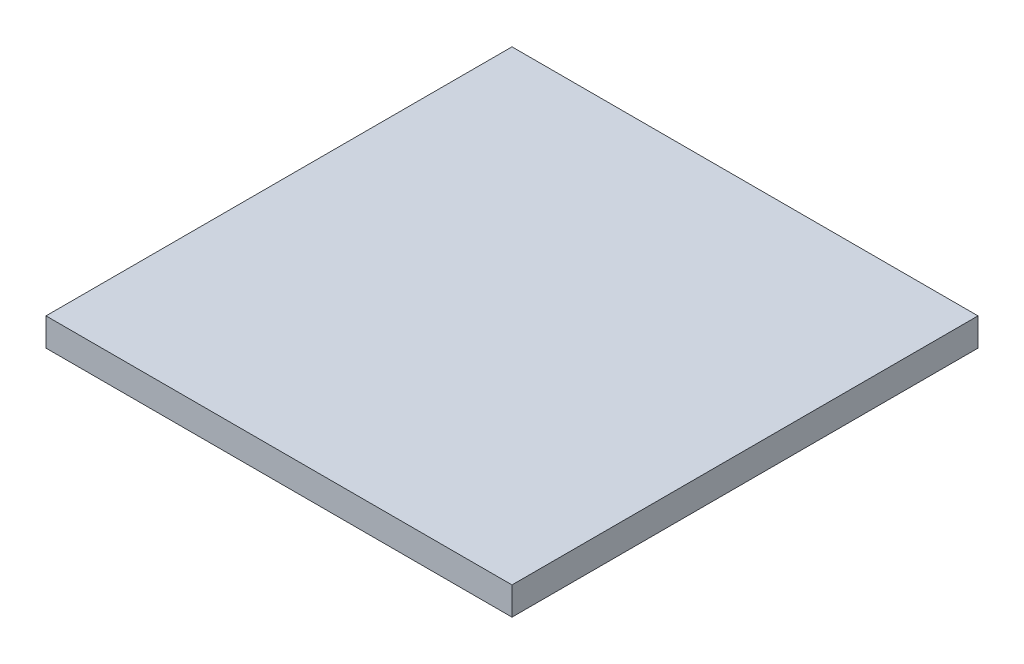
SolidWorks part; units mm, degrees
material "Acrylic (Medium-high impact)"
ref_plane "Front Plane" through (0, 0, 0) normal (0, 0, 1) x (1, 0, 0)
ref_plane "Top Plane" through (0, 0, 0) normal (0, 1, 0) x (1, 0, 0)
ref_plane "Right Plane" through (0, 0, 0) normal (1, 0, 0) x (0, 0, -1)
sketch "Sketch1" plane through (0, 0, 0) normal (0, 1, 0) x (1, 0, 0)
  line L1 (0, 0) -> (-50, 0)
  line L2 (0, 0) -> (0, 50)
  line L3 (0, 50) -> (-50, 50)
  line L4 (-50, 0) -> (-50, 50)
  dimension "D1" = 50
extrude "Boss-Extrude1" add sketch "Sketch1" along normal blind 3
